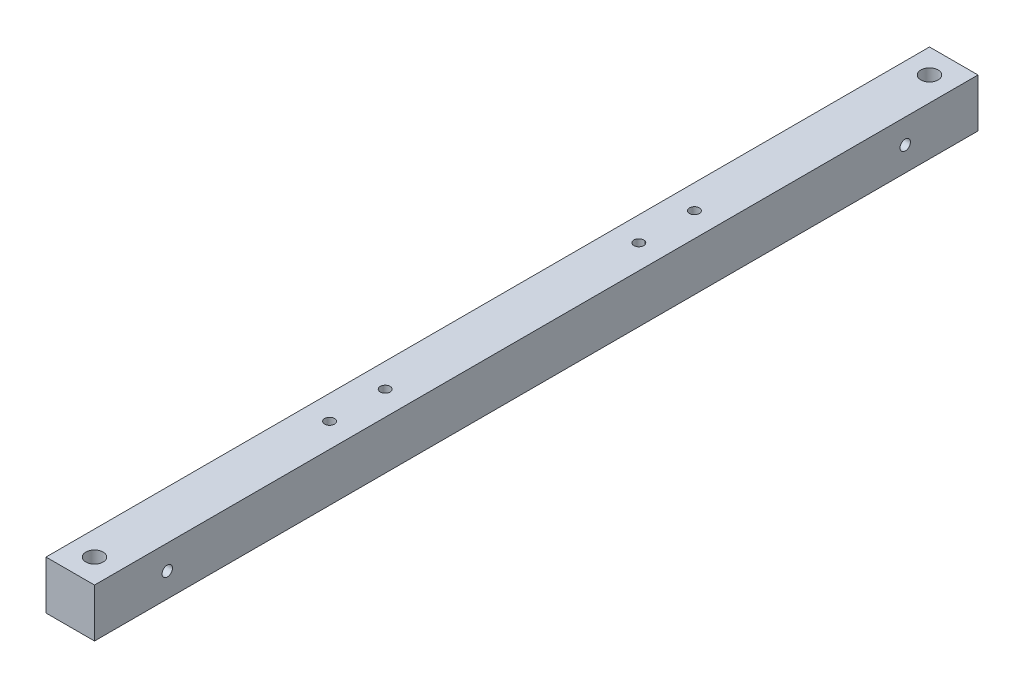
SolidWorks part; units mm, degrees
ref_plane "Ön Düzlem" through (0, 0, 0) normal (0, 0, 1) x (1, 0, 0)
ref_plane "Üst Düzlem" through (0, 0, 0) normal (0, 1, 0) x (1, 0, 0)
ref_plane "Sağ Düzlem" through (0, 0, 0) normal (1, 0, 0) x (0, 0, -1)
sketch "Çizim1" plane through (0, 0, 0) normal (0, 0, 1) x (1, 0, 0)
  line L1 (-14, -14) -> (14, -14)
  line L2 (-14, -14) -> (-14, 14)
  line L3 (-14, 14) -> (14, 14)
  line L4 (14, -14) -> (14, 14)
  line L5 (-14, -14) -> (14, 14) construction
  line L6 (-14, 14) -> (14, -14) construction
  point P0 (0, 0)
  dimension "D1" = 28
  dimension "D2" = 28
extrude "Yükseklik-Ekstrüzyon1" add sketch "Çizim1" along normal mid plane 510
sketch "Çizim2" plane through (14, 0, 0) normal (1, 0, 0) x (0, 0, -1)
  line L0 (-255, 14) -> (255, 14) construction
  line L1 (255, -14) -> (255, 14) construction
  line L2 (-255, -14) -> (-255, 14) construction
  circle A0 centre (213, 0) radius 3
  circle A1 centre (-213, 0) radius 3
  dimension "D1" = 14
  dimension "D2" = 6
  dimension "D3" = 6
  dimension "D5" = 42
  dimension "D4" = 42
  dimension "D6" = 14
extrude "Kes-Ekstrüzyon1" cut sketch "Çizim2" against normal blind 40
sketch "Çizim4" plane through (-14, 0, 0) normal (-1, 0, 0) x (0, 0, 1)
  circle A0 centre (-213, 0) radius 5
  circle A1 centre (213, 0) radius 5
  dimension "D1" = 10
extrude "Kes-Ekstrüzyon2" cut sketch "Çizim4" against normal blind 7
sketch "Çizim5" plane through (0, 14, 0) normal (0, 1, 0) x (1, 0, 0)
  line L1 (14, 255) -> (-14, 255) construction
  line L2 (14, -255) -> (-14, -255) construction
  circle A0 centre (0, -241) radius 3
  circle A1 centre (0, 241) radius 3
  dimension "D1" = 6
  dimension "D2" = 14
  dimension "D3" = 14
extrude "Kes-Ekstrüzyon3" cut sketch "Çizim5" against normal through all and the other way through all
sketch "Çizim6" plane through (0, 14, 0) normal (0, 1, 0) x (1, 0, 0)
  circle A0 centre (0, 241) radius 5
  circle A1 centre (0, -241) radius 5
  dimension "D1" = 10
extrude "Kes-Ekstrüzyon4" cut sketch "Çizim6" against normal blind 7
sketch "Çizim8" plane through (0, 14, 0) normal (0, 1, 0) x (1, 0, 0)
  line L0 (-14, 0) -> (14, 0) construction
  line L1 (-14, -255) -> (-14, 255) construction
  line L2 (14, -255) -> (14, 255) construction
  line L3 (-14, -255) -> (-14, 255) construction
  line L4 (0, -105.3) -> (0, -73.2) construction
  circle A0 centre (0, -105.3) radius 2.85
  circle A1 centre (0, -73.2) radius 2.85
  circle A2 centre (0, 73.2) radius 2.85
  circle A3 centre (0, 105.3) radius 2.85
  point P7 (-14, 0)
  point P11 (0, -89.25)
  point P13 (0, 0)
  dimension "D1" = 5.7
  dimension "D2" = 32.1
  dimension "D3" = 89.25
extrude "Kes-Ekstrüzyon6" cut sketch "Çizim8" against normal through all
